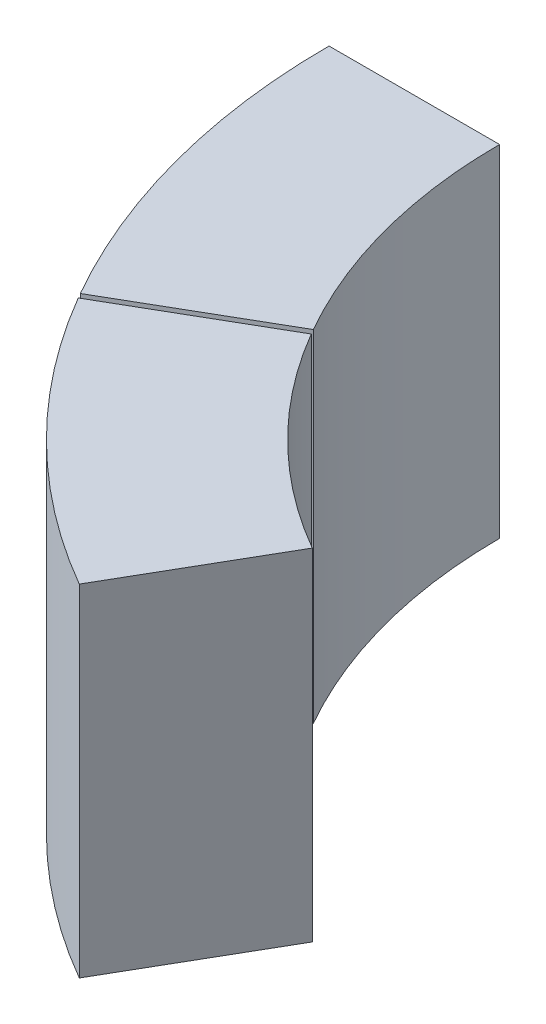
SolidWorks part; units mm, degrees
ref_plane "前视基准面" through (0, 0, 0) normal (0, 0, 1) x (1, 0, 0)
ref_plane "上视基准面" through (0, 0, 0) normal (0, 1, 0) x (1, 0, 0)
ref_plane "右视基准面" through (0, 0, 0) normal (1, 0, 0) x (0, 0, -1)
sketch "草图1" plane through (0, 0, 0) normal (0, 1, 0) x (1, 0, 0)
  line L0 (0, 0) -> (-1200, 0) construction
  line L1 (0, 0) -> (-600, -1039.2305) construction
  line L2 (-900, 0) -> (-1200, 0)
  line L3 (-450, -779.4229) -> (-600, -1039.2305)
  circle A0 centre (0, 0) radius 1200 construction
  circle A1 centre (0, 0) radius 900 construction
  arc A2 (-1200, 0) -> (-600, -1039.2305) centre (0, 0) ccw
  arc A3 (-900, 0) -> (-450, -779.4229) centre (0, 0) ccw
  dimension "D1" = 2400
  dimension "D2" = 1800
  dimension "D3" = 60
extrude "凸台-拉伸1" add sketch "草图1" along normal blind 600 contours A3 L2 A2 L3
sketch "草图2" plane through (0, 600, 0) normal (0, 1, 0) x (1, 0, 0)
  line L0 (0, 0) -> (-1039.2305, -600) construction
  line L1 (-57.7959, -27.595) -> (-1097.0264, -627.595)
  line L2 (-900, 0) -> (-1200, 0)
  line L3 (-600, -1039.2305) -> (-450, -779.4229)
  line L4 (-900, 0) -> (-1200, 0) construction
  line L5 (-600, -1039.2305) -> (-450, -779.4229) construction
  line L6 (-41.407, -29.6798) -> (-1080.6374, -629.6798)
  line L7 (-1097.0264, -627.595) -> (-1080.6374, -629.6798)
  line L8 (-57.7959, -27.595) -> (-41.407, -29.6798)
  arc A2 (-900, 0) -> (-450, -779.4229) centre (0, 0) ccw
  arc A3 (-1200, 0) -> (-600, -1039.2305) centre (0, 0) ccw
  arc A4 (-900, 0) -> (-450, -779.4229) centre (0, 0) ccw construction
  arc A5 (-1200, 0) -> (-600, -1039.2305) centre (0, 0) ccw construction
  dimension "D2" = 5
  dimension "D3" = 5
  dimension "D1" = 0
extrude "切除-拉伸1" cut sketch "草图2" against normal blind 600
sketch "草图3" plane through (0, 0, 0) normal (0, -1, 0) x (1, 0, 0)
  line L0 (-825.2121, 470.6629) -> (-998.4202, 570.6647)
  line L1 (-820.2121, 479.3232) -> (-993.4202, 579.3249)
  line L2 (-781.9108, 445.6629) -> (-1041.7215, 595.6647)
  line L3 (-1200, 0) -> (-900, 0)
  line L4 (-781.9108, 445.6629) -> (-1041.7215, 595.6647) construction
  line L5 (-1200, 0) -> (-900, 0) construction
  line L6 (-1036.7215, 604.3249) -> (-776.9108, 454.3232)
  line L7 (-450, 779.4229) -> (-600, 1039.2305)
  line L8 (-1036.7215, 604.3249) -> (-776.9108, 454.3232) construction
  line L9 (-450, 779.4229) -> (-600, 1039.2305) construction
  arc A0 (-825.2121, 470.6629) -> (-820.2121, 479.3232) centre (0, 0) cw
  arc A1 (-998.4202, 570.6647) -> (-993.4202, 579.3249) centre (0, 0) cw
  arc A2 (-781.9108, 445.6629) -> (-900, 0) centre (0, 0) ccw
  arc A3 (-1041.7215, 595.6647) -> (-1200, 0) centre (0, 0) ccw
  arc A4 (-781.9108, 445.6629) -> (-900, 0) centre (0, 0) ccw construction
  arc A5 (-1041.7215, 595.6647) -> (-1200, 0) centre (0, 0) ccw construction
  arc A6 (-600, 1039.2305) -> (-1036.7215, 604.3249) centre (0, 0) ccw
  arc A7 (-450, 779.4229) -> (-776.9108, 454.3232) centre (0, 0) ccw
  arc A8 (-600, 1039.2305) -> (-1036.7215, 604.3249) centre (0, 0) ccw construction
  arc A9 (-450, 779.4229) -> (-776.9108, 454.3232) centre (0, 0) ccw construction
  dimension "D3" = 50
  dimension "D4" = 50
  dimension "D1" = 0
  dimension "D2" = 0
extrude "凸台-拉伸2" add sketch "草图3" against normal blind 100
shell "抽壳1" thickness 10
sketch "草图4" plane through (0, 600, 0) normal (0, 1, 0) x (1, 0, 0)
  line L0 (-463.6328, -783.0355) -> (-603.6392, -1025.5338) construction
  line L1 (-1022.9884, -607.9431) -> (-780.476, -467.9286) construction
  line L2 (-909.9451, -10) -> (-1189.958, -10) construction
  line L3 (-795.476, -441.9478) -> (-1037.9884, -581.9623) construction
  line L4 (-463.6328, -783.0355) -> (-603.6392, -1025.5338)
  line L5 (-1022.9884, -607.9431) -> (-780.476, -467.9286)
  line L6 (-909.9451, -10) -> (-1189.958, -10)
  line L7 (-795.476, -441.9478) -> (-1037.9884, -581.9623)
  arc A0 (-780.476, -467.9286) -> (-463.6328, -783.0355) centre (0, 0) ccw construction
  arc A1 (-1022.9884, -607.9431) -> (-603.6392, -1025.5338) centre (0, 0) ccw construction
  arc A2 (-909.9451, -10) -> (-795.476, -441.9478) centre (0, 0) ccw construction
  arc A3 (-1189.958, -10) -> (-1037.9884, -581.9623) centre (0, 0) ccw construction
  arc A4 (-780.476, -467.9286) -> (-463.6328, -783.0355) centre (0, 0) ccw
  arc A5 (-1022.9884, -607.9431) -> (-603.6392, -1025.5338) centre (0, 0) ccw
  arc A6 (-909.9451, -10) -> (-795.476, -441.9478) centre (0, 0) ccw
  arc A7 (-1189.958, -10) -> (-1037.9884, -581.9623) centre (0, 0) ccw
extrude "凸台-拉伸3" add sketch "草图4" against normal blind 10
